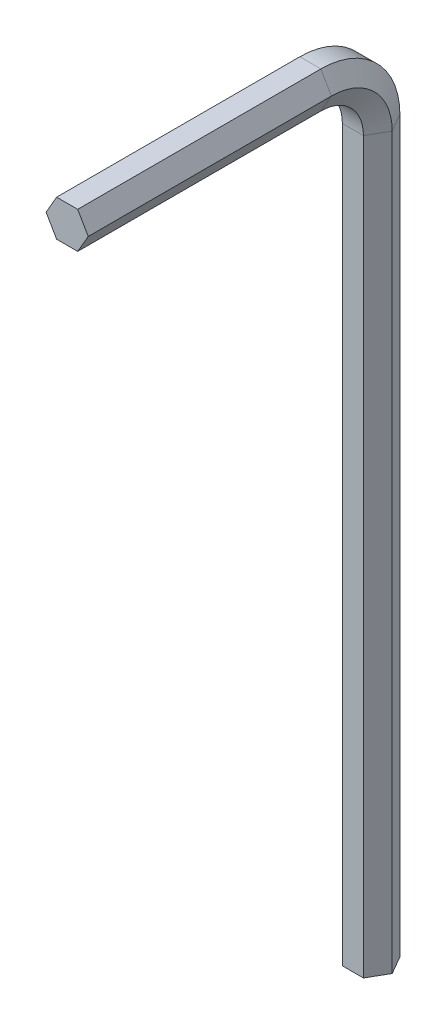
SolidWorks part; units mm, degrees
ref_plane "Front Plane" through (0, 0, 0) normal (0, 0, 1) x (1, 0, 0)
ref_plane "Top Plane" through (0, 0, 0) normal (0, 1, 0) x (1, 0, 0)
ref_plane "Right Plane" through (0, 0, 0) normal (1, 0, 0) x (0, 0, -1)
sketch "Çizim1" plane through (0, 0, 0) normal (0, 0, 1) x (1, 0, 0)
  line L1 (1.7321, 0) -> (0.866, 1.5)
  line L2 (0.866, 1.5) -> (-0.866, 1.5)
  line L3 (-0.866, 1.5) -> (-1.7321, 0)
  line L4 (-1.7321, 0) -> (-0.866, -1.5)
  line L5 (-0.866, -1.5) -> (0.866, -1.5)
  line L6 (0.866, -1.5) -> (1.7321, 0)
  circle A0 centre (0, 0) radius 1.5 construction
  dimension "D1" = 3
sketch "Çizim2" plane through (0, 0, 0) normal (1, 0, 0) x (0, 0, -1)
  line L0 (0, 0) -> (20, 0)
  line L1 (25, -5) -> (25, -65)
  arc A0 (20, 0) -> (25, -5) centre (20, -5) cw
  point P6 (25, 0)
  dimension "D3" = 5
  dimension "D1" = 25
  dimension "D2" = 65
sweep "Süpür1" add profiles "Çizim1" path "Çizim2"
